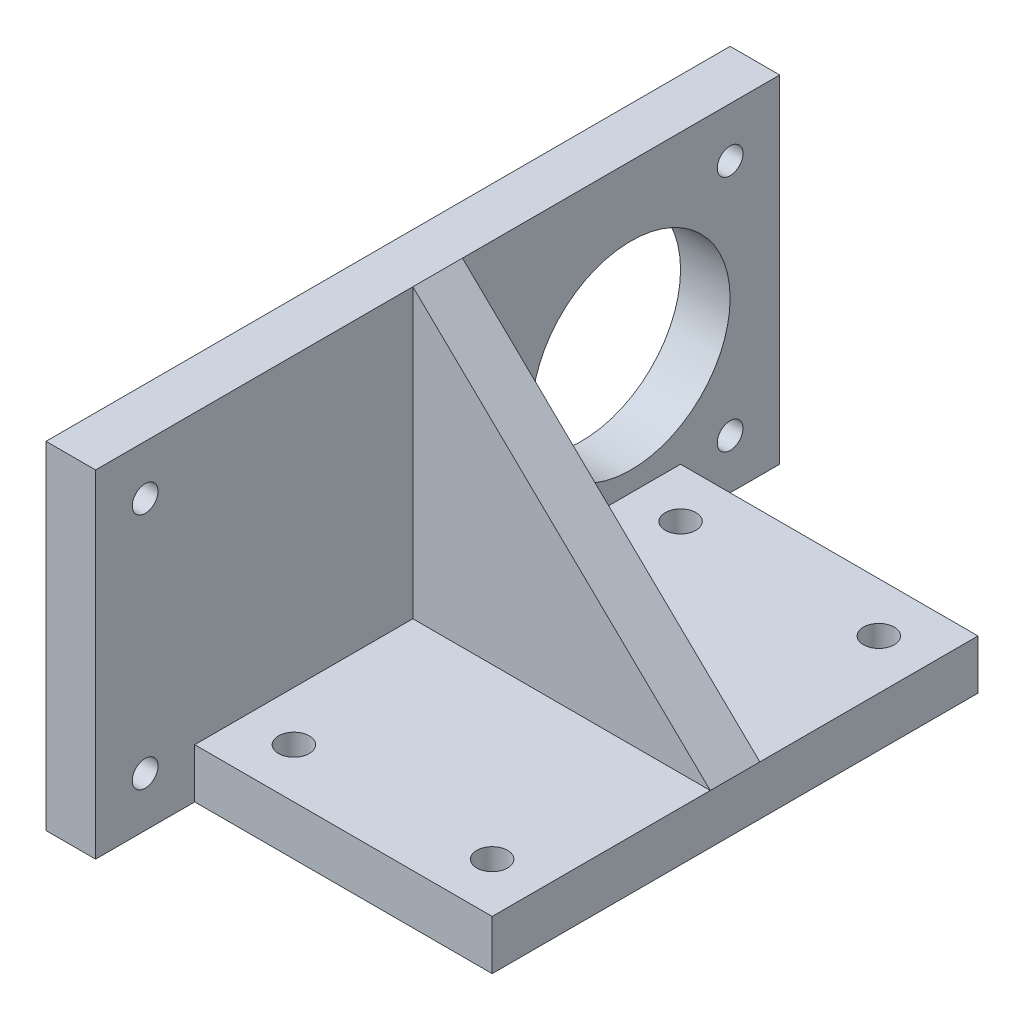
SolidWorks part; units mm, degrees
ref_plane "Front Plane" through (0, 0, 0) normal (0, 0, 1) x (1, 0, 0)
ref_plane "Top Plane" through (0, 0, 0) normal (0, 1, 0) x (1, 0, 0)
ref_plane "Right Plane" through (0, 0, 0) normal (1, 0, 0) x (0, 0, -1)
sketch "Sketch1" plane through (0, 0, 0) normal (1, 0, 0) x (0, 0, -1)
  line L0 (55, 0) -> (-55, 0) construction
  line L5 (-29.5, 12) -> (29.5, -12) construction
  line L6 (-29.5, -12) -> (29.5, 12) construction
  line L7 (-34.5, 17) -> (34.5, 17)
  line L8 (-34.5, 17) -> (-34.5, -17)
  line L9 (-34.5, -17) -> (34.5, -17)
  line L10 (34.5, 17) -> (34.5, -17)
  circle A0 centre (-29.5, 12) radius 1.3
  circle A1 centre (-29.5, -12) radius 1.3
  circle A2 centre (29.5, 12) radius 1.3
  circle A3 centre (29.5, -12) radius 1.3
  circle A4 centre (19.5, 0) radius 10
  point P0 (0, 0)
  point P1 (-19.5, 0)
  dimension "D1" = 2.6
  dimension "D3" = 59
  dimension "D9" = 20
  dimension "D2" = 24
  dimension "D4" = 5
  dimension "D5" = 5
  dimension "D6" = 5
  dimension "D7" = 5
  dimension "D8" = 10
extrude "Boss-Extrude1" add sketch "Sketch1" along normal blind 5
sketch "Sketch2" plane through (5, 0, 0) normal (1, 0, 0) x (0, 0, -1)
  line L0 (-34.5, -17) -> (34.5, -17) construction
  line L1 (-24.5, -17) -> (24.5, -17)
  line L2 (-24.5, -17) -> (-24.5, -12)
  line L3 (-24.5, -12) -> (24.5, -12)
  line L4 (24.5, -17) -> (24.5, -12)
  line L5 (-34.5, 17) -> (-34.5, -17) construction
  line L6 (34.5, -17) -> (34.5, 17) construction
  dimension "D1" = 10
  dimension "D2" = 10
  dimension "D3" = 5
extrude "Boss-Extrude2" add sketch "Sketch2" along normal blind 30
sketch "Sketch3" plane through (0, 0, 0) normal (0, 0, 1) x (1, 0, 0)
  line L0 (5, -12) -> (35, -12)
  line L1 (35, -12) -> (5, 17)
  line L2 (5, 17) -> (5, -12)
extrude "Boss-Extrude3" add sketch "Sketch3" along normal mid plane 5
sketch "Sketch4" plane through (0, -17, 0) normal (0, -1, 0) x (1, 0, 0)
  line L0 (35, 24.5) -> (35, -24.5) construction
  line L1 (35, 24.5) -> (5, 24.5) construction
  line L2 (55, 0) -> (-55, 0) construction
  circle A0 centre (30, 19.5) radius 1.55
  circle A2 centre (10, 19.5) radius 1.55
  circle A3 centre (10, -19.5) radius 1.55
  circle A4 centre (30, -19.5) radius 1.55
  point P14 (10, 19.5)
  dimension "D1" = 3.1
  dimension "D2" = 5
  dimension "D3" = 5
  dimension "D4" = 20
extrude "Cut-Extrude1" cut sketch "Sketch4" against normal blind 5
